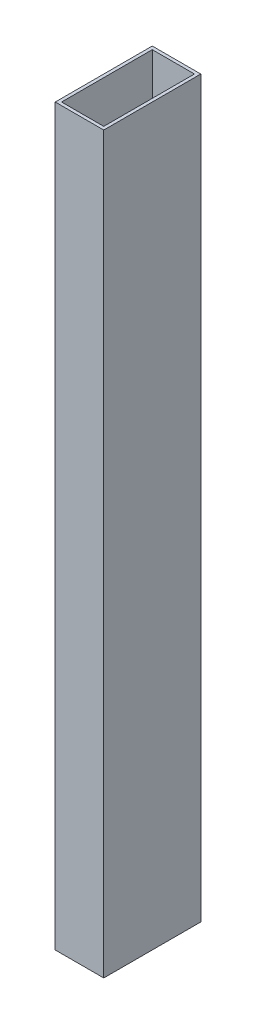
SolidWorks part; units mm, degrees
material "6061 Alloy"
ref_plane "Front Plane" through (0, 0, 0) normal (0, 0, 1) x (1, 0, 0)
ref_plane "Top Plane" through (0, 0, 0) normal (0, 1, 0) x (1, 0, 0)
ref_plane "Right Plane" through (0, 0, 0) normal (1, 0, 0) x (0, 0, -1)
sketch "Sketch1" plane through (0, 0, 0) normal (0, 1, 0) x (1, 0, 0)
  line L1 (-12.7, 25.4) -> (12.7, 25.4)
  line L2 (-12.7, 25.4) -> (-12.7, -25.4)
  line L3 (-12.7, -25.4) -> (12.7, -25.4)
  line L4 (12.7, 25.4) -> (12.7, -25.4)
  line L5 (-12.7, 25.4) -> (12.7, -25.4) construction
  line L6 (-12.7, -25.4) -> (12.7, 25.4) construction
  point P0 (0, 0)
  dimension "D1" = 50.8
  dimension "D2" = 25.4
extrude "Boss-Extrude1" add sketch "Sketch1" along normal blind 384.556
sketch "Sketch2" plane through (0, 0, 0) normal (0, -1, 0) x (1, 0, 0)
  line L0 (12.7, 25.4) -> (12.7, -25.4) construction
  line L1 (11.049, 23.749) -> (-11.049, 23.749)
  line L2 (11.049, 23.749) -> (11.049, -23.749)
  line L3 (11.049, -23.749) -> (-11.049, -23.749)
  line L4 (-11.049, 23.749) -> (-11.049, -23.749)
  line L5 (11.049, 23.749) -> (-11.049, -23.749) construction
  line L6 (11.049, -23.749) -> (-11.049, 23.749) construction
  line L7 (12.7, -25.4) -> (-12.7, -25.4) construction
  line L8 (-12.7, -25.4) -> (-12.7, 25.4) construction
  line L9 (-12.7, 25.4) -> (12.7, 25.4) construction
  point P0 (0, 0)
  dimension "D1" = 1.651
  dimension "D2" = 1.651
  dimension "D3" = 1.651
  dimension "D4" = 1.651
extrude "Cut-Extrude1" cut sketch "Sketch2" against normal through all and the other way through all
ref_plane "Plane1" through (0, 192.278, 0) normal (0, 1, 0) x (1, 0, 0)
